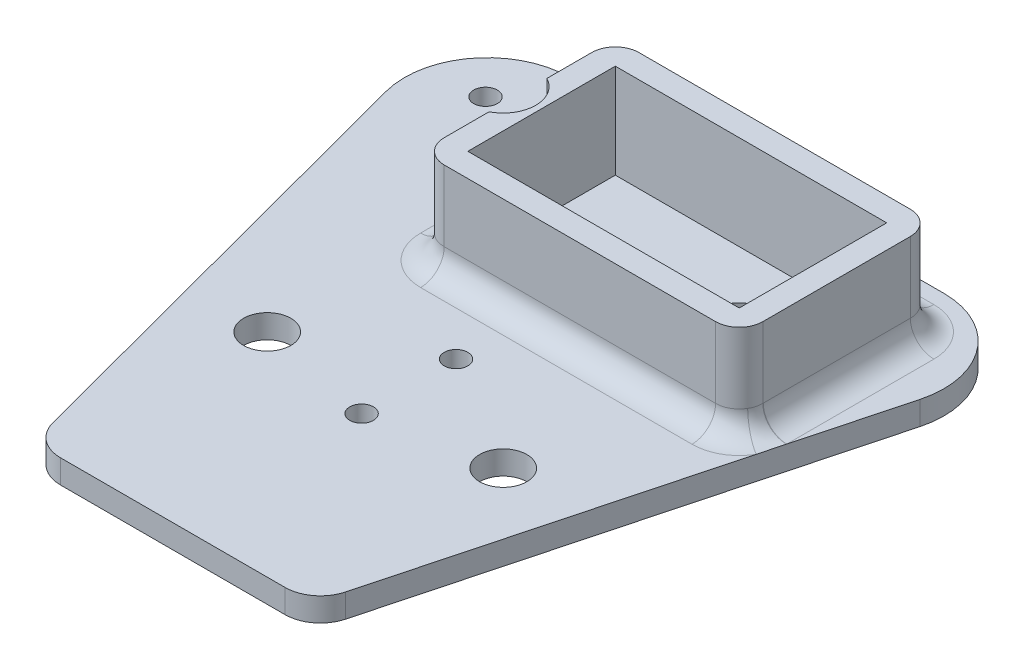
SolidWorks part; units mm, degrees
ref_plane "Front Plane" through (0, 0, 0) normal (0, 0, 1) x (1, 0, 0)
ref_plane "Top Plane" through (0, 0, 0) normal (0, 1, 0) x (1, 0, 0)
ref_plane "Right Plane" through (0, 0, 0) normal (1, 0, 0) x (0, 0, -1)
sketch "Sketch1" plane through (0, 0, 0) normal (0, 1, 0) x (1, 0, 0)
  line L0 (-56.7778, 0) -> (59.7945, 0) construction
  line L1 (0, 76.0508) -> (0, -42.0716) construction
  line L3 (15, 0) -> (24.9488, 37.5)
  line L4 (24.9488, 37.5) -> (-24.9488, 37.5)
  line L5 (-24.9488, 37.5) -> (-15, 0)
  line L6 (10, -35.718) -> (10, 52.392) construction
  line L7 (-58.5565, 6) -> (66.0263, 6) construction
  line L8 (-56.7778, 26) -> (55.9498, 26) construction
  line L9 (-11.8164, -12) -> (11.8164, -12)
  line L10 (-15, 0) -> (-11.8164, -12)
  line L11 (15, 0) -> (11.8164, -12)
  circle A0 centre (10, 26) radius 3
  circle A1 centre (10, 6) radius 2
  circle A2 centre (-10, 6) radius 2
  circle A4 centre (10, 26) radius 11.5 construction
  dimension "D7" = 6
  dimension "D5" = 23
  dimension "D6" = 4
  dimension "D1" = 10
  dimension "D2" = 30
  dimension "D3" = 6
  dimension "D4" = 20
extrude "Boss-Extrude1" add sketch "Sketch1" along normal blind 2
fillet "Fillet1" radius 7 2 edges at (24.9488, 1, -37.5) (-24.9488, 1, -37.5)
sketch "Sketch3" plane through (0, 2, 0) normal (0, 1, 0) x (1, 0, 0)
  line L0 (-10, 26) -> (42.6633, 26) construction
  line L1 (10, 26) -> (10, 52.4248) construction
  line L2 (-6.75, 19.75) -> (16.25, 19.75)
  line L3 (-6.75, 19.75) -> (-6.75, 32.25)
  line L4 (-6.75, 32.25) -> (16.25, 32.25)
  line L5 (16.25, 19.75) -> (16.25, 32.25)
  line L6 (-8.75, 34.25) -> (18.25, 34.25)
  line L7 (18.25, 17.75) -> (18.25, 34.25)
  line L8 (-8.75, 17.75) -> (18.25, 17.75)
  line L9 (-8.75, 17.75) -> (-8.75, 34.25)
  dimension "D1" = 12.5
  dimension "D2" = 23
  dimension "D3" = 6.25
  dimension "D4" = 2
extrude "Boss-Extrude2" add sketch "Sketch3" along normal blind 8
fillet "Fillet2" radius 2 4 edges at (-8.75, 6, -17.75) (18.25, 6, -17.75) (18.25, 6, -34.25) (-8.75, 6, -34.25)
fillet "Fillet3" radius 2 8 edges at (-8.1642, 2, -33.6642) (4.75, 2, -34.25) (17.6642, 2, -33.6642) (18.25, 2, -26) (17.6642, 2, -18.3358) (4.75, 2, -17.75) (-8.1642, 2, -18.3358) (-8.75, 2, -26)
sketch "Sketch2" plane through (0, 2, 0) normal (0, 1, 0) x (1, 0, 0)
  line L0 (0, -18.0124) -> (0, 52.2423) construction
  line L1 (-42.0895, 12) -> (41.773, 12) construction
  line L2 (-47.0474, 32.5) -> (41.773, 32.5) construction
  line L3 (-9.615, 0) -> (9.615, 0) construction
  line L4 (15.8495, 37.5) -> (-15.8495, 37.5) construction
  line L5 (10, 26) -> (-43.4257, 26) construction
  circle A0 centre (10, 26) radius 10 construction
  circle A1 centre (0, 34.5) radius 1
  circle A3 centre (18, 32.5) radius 1
  circle A4 centre (0, 4) radius 1
  circle A6 centre (0, 12) radius 1
  circle A8 centre (-18, 32.5) radius 1
  dimension "D1" = 20
  dimension "D4" = 2
  dimension "D5" = 2
  dimension "D7" = 2
  dimension "D8" = 2
  dimension "D2" = 12
  dimension "D3" = 5
  dimension "D9" = 3
  dimension "D10" = 18
  dimension "D12" = 8
extrude "Cut-Extrude1" cut sketch "Sketch2" against normal blind 2
sketch "Sketch4" plane through (0, 2, 0) normal (0, 1, 0) x (1, 0, 0)
  line L0 (0, -8.7295) -> (0, 49.4996) construction
  line L1 (10, 26) -> (-59.7059, 26) construction
  circle A0 centre (-10, 26) radius 2
  dimension "D1" = 4
  dimension "D2" = 10
extrude "Cut-Extrude2" cut sketch "Sketch4" against normal through all both and the other way through all
sketch "Sketch5" plane through (0, 2, 0) normal (0, 1, 0) x (1, 0, 0)
  circle A0 centre (-10, 26) radius 2.75
  dimension "D1" = 5.5
extrude "Cut-Extrude3" cut sketch "Sketch5" along normal through all
fillet "Fillet4" radius 3 2 edges at (11.8164, 1, 12) (-11.8164, 1, 12)
